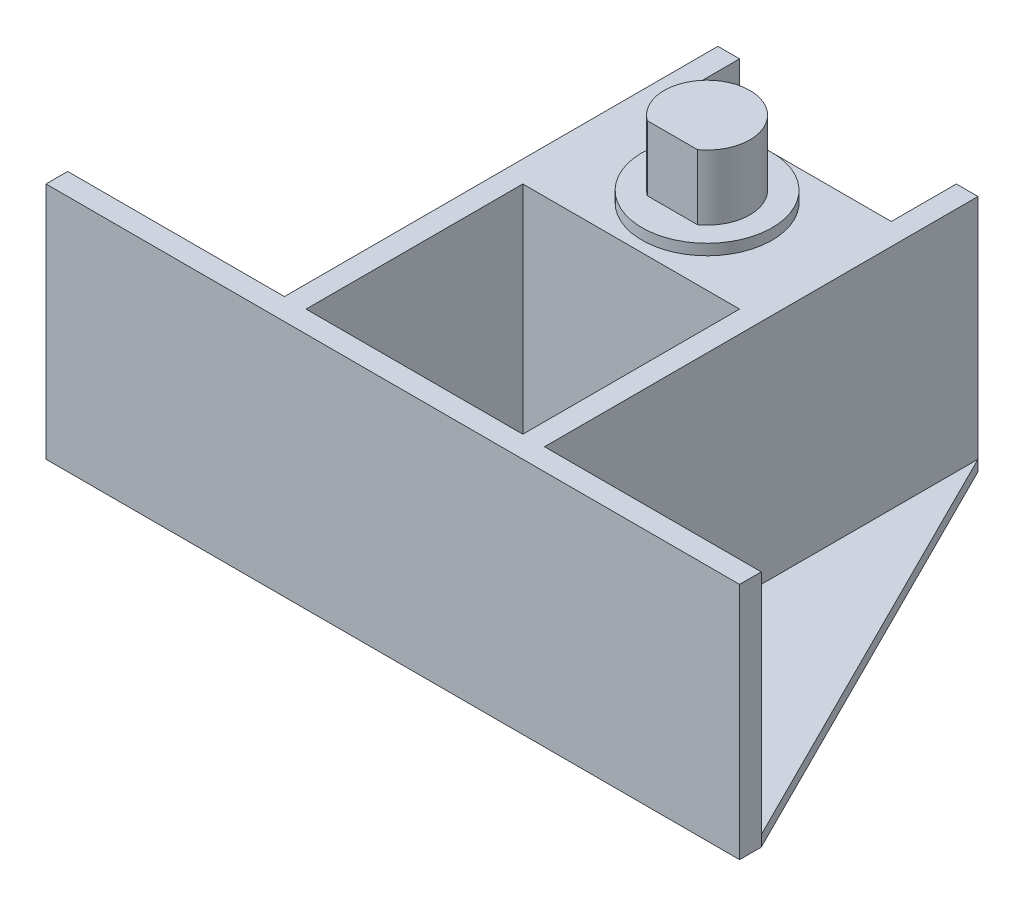
SolidWorks part; units mm, degrees
ref_plane "Front Plane" through (0, 0, 0) normal (0, 0, 1) x (1, 0, 0)
ref_plane "Top Plane" through (0, 0, 0) normal (0, 1, 0) x (1, 0, 0)
ref_plane "Right Plane" through (0, 0, 0) normal (1, 0, 0) x (0, 0, -1)
sketch "Sketch1" plane through (0, 0, 0) normal (0, 1, 0) x (1, 0, 0)
  circle A0 centre (0, 0) radius 3.95
  dimension "D1" = 7.9
extrude "Boss-Extrude1" add sketch "Sketch1" along normal blind 6
sketch "Sketch2" plane through (0, 0, 0) normal (0, -1, 0) x (1, 0, 0)
  circle A0 centre (0, 0) radius 6
  dimension "D1" = 12
extrude "Boss-Extrude2" add sketch "Sketch2" along normal blind 1
sketch "Sketch3" plane through (0, -1, 0) normal (0, -1, 0) x (1, 0, 0)
  line L1 (-12, -13) -> (12, -13)
  line L2 (-12, -13) -> (-12, 13)
  line L3 (-12, 13) -> (12, 13)
  line L4 (12, -13) -> (12, 13)
  line L5 (-12, -13) -> (12, 13) construction
  line L6 (-12, 13) -> (12, -13) construction
  line L7 (12, 13) -> (-12, 13)
  line L8 (12, 13) -> (12, 27)
  line L9 (12, 27) -> (-12, 27)
  line L10 (-12, 13) -> (-12, 27)
  point P0 (0, 0)
  circle M5 centre (0, 0) radius 6
  dimension "D1" = 13
  dimension "D2" = 24
  dimension "D3" = 40
extrude "Boss-Extrude3" add sketch "Sketch3" along normal blind 21 contours L10 L3 L8 L9 | L1 L4 L3 L2 M5 | M5
sketch "Sketch6" plane through (0, -22, 0) normal (0, -1, 0) x (1, 0, 0)
  line L0 (12, 27) -> (-12, 27) construction
  line L1 (-32, 27) -> (32, 27)
  line L2 (-32, 27) -> (-32, 29)
  line L3 (-32, 29) -> (32, 29)
  line L4 (32, 27) -> (32, 29)
  line L5 (-12, -13) -> (-12, 27) construction
  line L6 (12, -13) -> (12, 27) construction
  dimension "D1" = 20
  dimension "D2" = 20
  dimension "D3" = 2
extrude "Boss-Extrude5" add sketch "Sketch6" against normal up to surface (21 mm away) up to face at (0, -1, -6)
sketch "Sketch8" plane through (0, -1, 0) normal (0, 1, 0) x (1, 0, 0)
  line L0 (32, -27) -> (12, -27) construction
  line L1 (10, -27) -> (-10, -27)
  line L2 (10, -27) -> (10, -7)
  line L3 (10, -7) -> (-10, -7)
  line L4 (-10, -27) -> (-10, -7)
  line L5 (12, 13) -> (12, -27) construction
  line L6 (-12, 13) -> (-12, -27) construction
  line L7 (-12, 13) -> (12, 13) construction
  line L8 (0, 0) -> (0, -7) construction
  line L9 (10, 13) -> (-10, 13)
  line L10 (10, 13) -> (10, 7)
  line L11 (10, 7) -> (-10, 7)
  line L12 (-10, 13) -> (-10, 7)
  line L13 (0, 0) -> (0, 7) construction
  dimension "D1" = 2
  dimension "D2" = 2
  dimension "D3" = 20
extrude "Cut-Extrude1" cut sketch "Sketch8" against normal through all
sketch "Sketch9" plane through (0, 6, 0) normal (0, 1, 0) x (1, 0, 0)
  line L0 (0, 0) -> (0, -3.95) construction
  line L2 (2.3157, -4.7) -> (-2.3157, -4.7)
  line L3 (2.3157, -4.7) -> (2.3157, -3.2)
  line L4 (2.3157, -3.2) -> (-2.3157, -3.2)
  line L5 (-2.3157, -4.7) -> (-2.3157, -3.2)
  line L6 (2.3157, -4.7) -> (-2.3157, -3.2) construction
  line L7 (2.3157, -3.2) -> (-2.3157, -4.7) construction
  circle A0 centre (0, 0) radius 3.95 construction
  dimension "D1" = 0.75
extrude "Cut-Extrude2" cut sketch "Sketch9" against normal up to surface (6 mm away) up to face at (0, 0, 3.95)
sketch "Sketch10" plane through (0, -22, 0) normal (0, -1, 0) x (1, 0, 0)
  line L0 (-12, -13) -> (-10, -13) construction
  line L1 (-32, 29) -> (32, 29)
  line L2 (-32, 29) -> (-32, 27)
  line L3 (-12, -13) -> (12, -13)
  line L4 (32, 29) -> (32, 27)
  line L5 (32, 27) -> (32, 29) construction
  line L6 (32, 27) -> (12, -13)
  line L7 (-12, -13) -> (-32, 27)
extrude "Boss-Extrude6" add sketch "Sketch10" along normal blind 1
sketch "Sketch11" plane through (0, -22, 0) normal (0, 1, 0) x (1, 0, 0)
  line L4 (-10, -27) -> (10, -27)
  line L5 (10, -27) -> (10, -7)
  line L6 (10, -7) -> (-10, -7)
  line L7 (-10, -7) -> (-10, -27)
  line L8 (-10, -27) -> (10, -27)
  line L9 (10, -27) -> (10, -7)
  line L10 (10, -7) -> (-10, -7)
  line L11 (-10, -7) -> (-10, -27)
  dimension "D1" = 0
extrude "Cut-Extrude3" cut sketch "Sketch11" against normal through all
